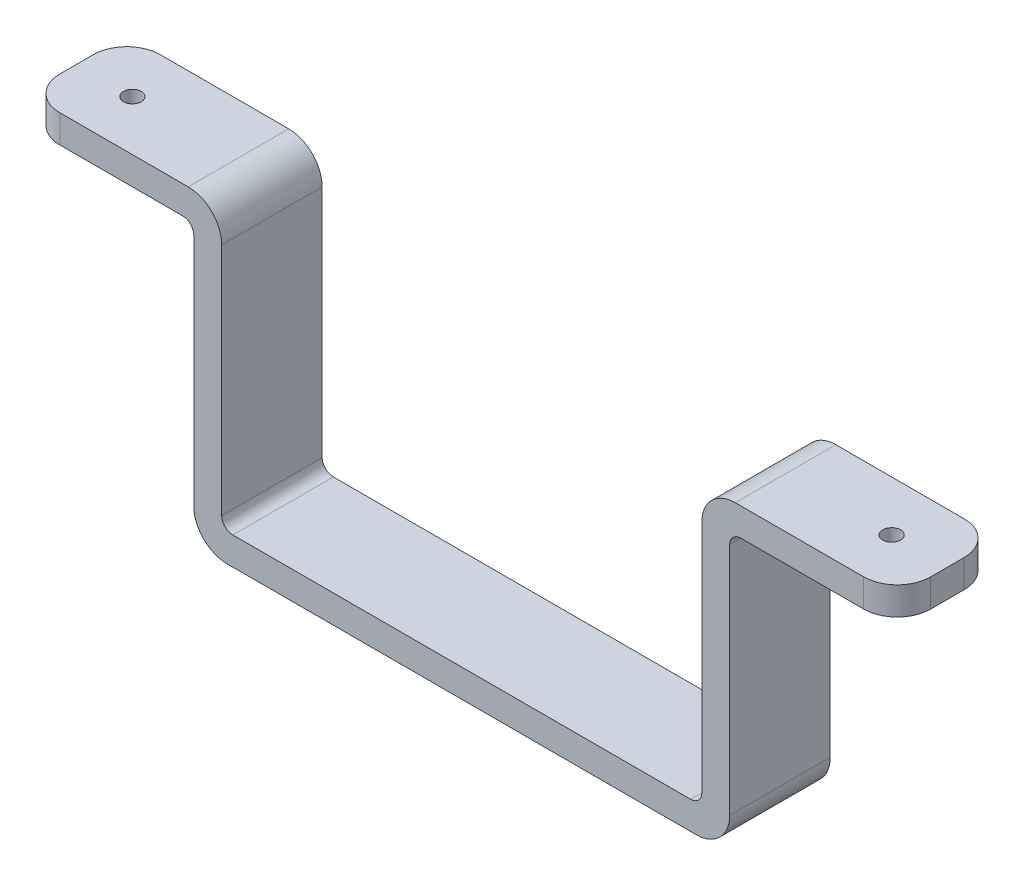
SolidWorks part; units mm, degrees
ref_plane "Front Plane" through (0, 0, 0) normal (0, 0, 1) x (1, 0, 0)
ref_plane "Top Plane" through (0, 0, 0) normal (0, 1, 0) x (1, 0, 0)
ref_plane "Right Plane" through (0, 0, 0) normal (1, 0, 0) x (0, 0, -1)
sketch "Sketch1" plane through (0, 0, 0) normal (0, 0, 1) x (1, 0, 0)
  line L0 (-45.4805, -17.3544) -> (-45.4805, 7.6456)
  line L1 (-45.4805, -17.3544) -> (2.5195, -17.3544)
  line L2 (2.5195, -17.3544) -> (2.5195, 7.6456)
  line L3 (-60.4805, 7.6456) -> (-45.4805, 7.6456)
  line L4 (2.5195, 7.6456) -> (17.5195, 7.6456)
  line L5 (0.0195, 10.1456) -> (17.5195, 10.1456)
  line L6 (0.0195, -14.8544) -> (0.0195, 10.1456)
  line L7 (-42.9805, -14.8544) -> (0.0195, -14.8544)
  line L8 (-42.9805, -14.8544) -> (-42.9805, 10.1456)
  line L9 (-60.4805, 10.1456) -> (-42.9805, 10.1456)
  line L10 (17.5195, 7.6456) -> (17.5195, 10.1456)
  line L11 (-60.4805, 10.1456) -> (-60.4805, 7.6456)
  point P7 (-21.4805, 7.6456)
  dimension "D1" = 25
  dimension "D2" = 48
  dimension "D3" = 2.5
extrude "Boss-Extrude1" add sketch "Sketch1" along normal blind 9
sketch "Sketch2" plane through (0, 10.1456, 0) normal (0, 1, 0) x (1, 0, 0)
  line L0 (-60.4805, -4.5) -> (-55.4805, -4.5) construction
  line L1 (-60.4805, -9) -> (-60.4805, 0) construction
  line L2 (-21.4805, 0) -> (-21.4805, -9) construction
  line L3 (0.0195, 0) -> (-42.9805, 0) construction
  line L4 (0.0195, -9) -> (-42.9805, -9) construction
  circle A0 centre (-55.4805, -4.5) radius 0.8
  circle A1 centre (12.5195, -4.5) radius 0.8
  dimension "D2" = 1.6
  dimension "D1" = 5
extrude "Cut-Extrude1" cut sketch "Sketch2" against normal blind 9
fillet "Fillet1" radius 1 4 edges at (2.5195, 7.6456, 4.5) (0.0195, -14.8544, 4.5) (-42.9805, -14.8544, 4.5) (-45.4805, 7.6456, 4.5)
fillet "Fillet2" radius 3 4 edges at (0.0195, 10.1456, 4.5) (2.5195, -17.3544, 4.5) (-45.4805, -17.3544, 4.5) (-42.9805, 10.1456, 4.5)
fillet "Fillet3" radius 3 4 edges at (17.5195, 8.8956, 9) (17.5195, 8.8956, 0) (-60.4805, 8.8956, 9) (-60.4805, 8.8956, 0)
